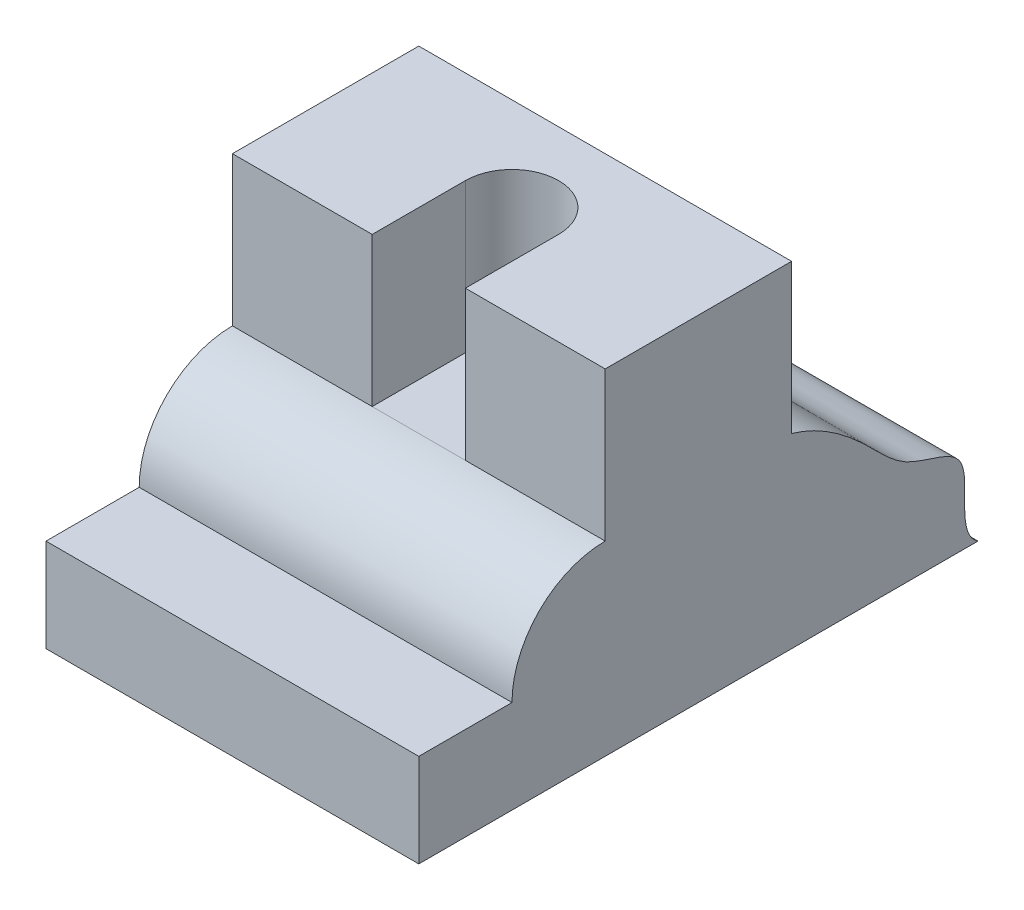
SolidWorks part; units mm, degrees
ref_plane "前视基准面" through (0, 0, 0) normal (0, 0, 1) x (1, 0, 0)
ref_plane "上视基准面" through (0, 0, 0) normal (0, 1, 0) x (1, 0, 0)
ref_plane "右视基准面" through (0, 0, 0) normal (1, 0, 0) x (0, 0, -1)
other "Configuration Table"
sketch "草图1" plane through (0, 0, 0) normal (0, 1, 0) x (1, 0, 0)
  line L1 (-100, -50) -> (100, -50)
  line L2 (-100, -50) -> (-100, 50)
  line L3 (-100, 50) -> (100, 50)
  line L4 (100, -50) -> (100, 50)
  line L5 (-100, -50) -> (100, 50) construction
  line L6 (-100, 50) -> (100, -50) construction
  point P0 (0, 0)
extrude "凸台-拉伸1" add sketch "草图1" along normal blind 100
sketch "草图2" plane through (-100, 0, 0) normal (-1, 0, 0) x (0, 0, 1)
  line L0 (50, 100) -> (50, 0) construction
  line L1 (50, 100) -> (50, 50)
  line L3 (100, 50) -> (150, 50)
  line L4 (150, 50) -> (150, 0)
  line L5 (150, 0) -> (50, 0)
  line L6 (50, 50) -> (50, 0)
  arc A0 (100, 50) -> (50, 100) centre (50, 50) ccw
extrude "凸台-拉伸2" add sketch "草图2" against normal blind 200
sketch "草图3" plane through (-100, 0, 0) normal (-1, 0, 0) x (0, 0, 1)
  line L0 (-50, 0) -> (-150, 0)
  line L1 (-50, 0) -> (-50, 100)
  spline S0 degree 3 poles (-50, 100) (-66.7214, 95.1223) (-87.6218, 78.4455) (-111.4276, 51.7988) (-153.7885, 47.4008) (-137.1407, 8.5683) (-150, 0) knots 0 0 0 0 0.338265 0.517817 0.712667 1 1 1 1
extrude "凸台-拉伸3" add sketch "草图3" against normal blind 200
sketch "草图4" plane through (0, 100, 0) normal (0, 1, 0) x (1, 0, 0)
  line L0 (0, -50) -> (0, 50) construction
  line L1 (100, -50) -> (25, -50)
  line L2 (100, -50) -> (100, 50)
  line L3 (100, 50) -> (-100, 50)
  line L4 (-100, -50) -> (-100, 50)
  line L5 (100, -50) -> (-100, 50) construction
  line L6 (100, 50) -> (-100, -50) construction
  line L7 (0, 50) -> (0, 25) construction
  line L8 (-25, 0) -> (-25, -50)
  line L9 (25, 0) -> (25, -50)
  line L10 (-25, -50) -> (-100, -50)
  arc A0 (25, 0) -> (-25, 0) centre (0, 0) ccw
  point P0 (0, 0)
extrude "凸台-拉伸5" add sketch "草图4" along normal blind 80
